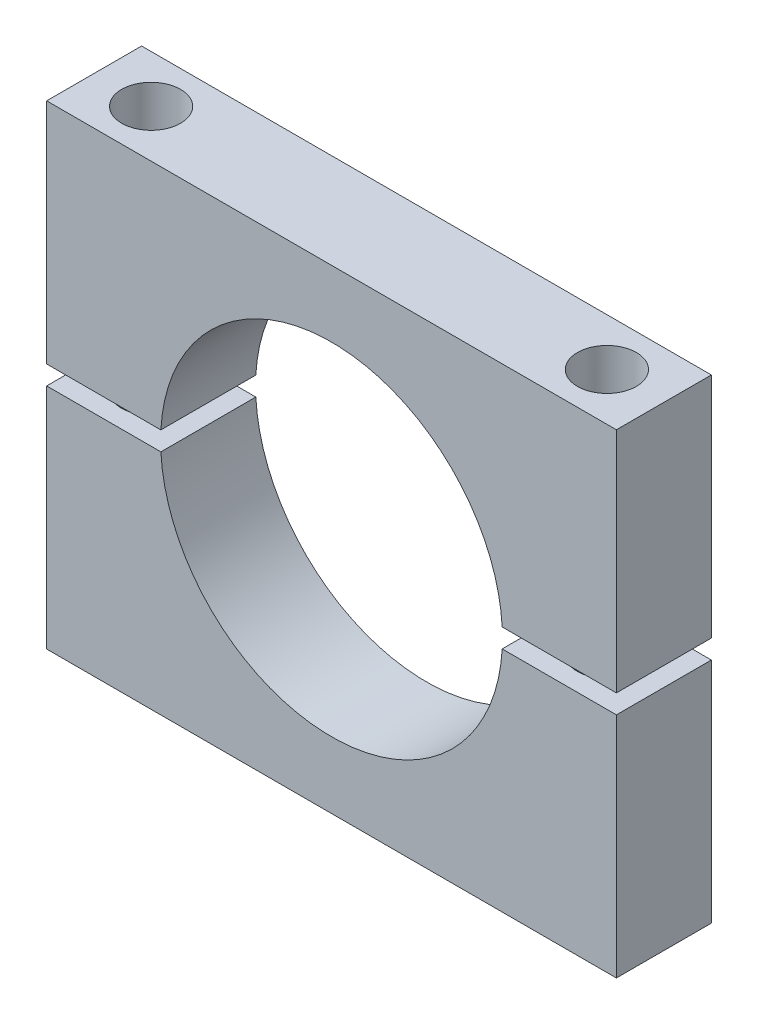
SolidWorks part; units mm, degrees
ref_plane "前视基准面" through (0, 0, 0) normal (0, 0, 1) x (1, 0, 0)
ref_plane "上视基准面" through (0, 0, 0) normal (0, 1, 0) x (1, 0, 0)
ref_plane "右视基准面" through (0, 0, 0) normal (1, 0, 0) x (0, 0, -1)
sketch "草图1" plane through (0, 0, 0) normal (0, 1, 0) x (1, 0, 0)
  line L1 (15, -2.5) -> (-15, -2.5)
  line L2 (15, -2.5) -> (15, 2.5)
  line L3 (15, 2.5) -> (-15, 2.5)
  line L4 (-15, -2.5) -> (-15, 2.5)
  line L5 (15, -2.5) -> (-15, 2.5) construction
  line L6 (15, 2.5) -> (-15, -2.5) construction
  point P0 (0, 0)
  dimension "D1" = 5
  dimension "D2" = 30
extrude "凸台-拉伸1" add sketch "草图1" along normal blind 25
sketch "草图2" plane through (0, 0, 2.5) normal (0, 0, 1) x (1, 0, 0)
  line L0 (15, 25) -> (-15, 0) construction
  line L1 (-15, 25) -> (15, 0) construction
  line L2 (-15, 12.5) -> (15, 12.5) construction
  line L3 (-15, 25) -> (-15, 0) construction
  line L4 (15, 25) -> (15, 0) construction
  line L5 (-15, 12) -> (-8.9861, 12)
  line L6 (-15, 13) -> (-8.9861, 13)
  line L7 (15, 13) -> (15, 12)
  line L8 (-15, 13) -> (-15, 12)
  line L10 (-15, 13) -> (15, 13) construction
  line L12 (-15, 12) -> (15, 12) construction
  line L13 (8.9861, 13) -> (15, 13)
  line L14 (8.9861, 12) -> (15, 12)
  arc A0 (-8.9861, 12) -> (8.9861, 12) centre (0, 12.5) ccw
  arc A1 (8.9861, 13) -> (-8.9861, 13) centre (0, 12.5) ccw
  dimension "D1" = 18
  dimension "D2" = 0.5
  dimension "D3" = 0.5
extrude "切除-拉伸1" cut sketch "草图2" against normal blind 21
sketch "草图3" plane through (0, 25, 0) normal (0, 1, 0) x (1, 0, 0)
  line L0 (-15, 0) -> (0, 0) construction
  line L1 (-15, 2.5) -> (-15, -2.5) construction
  line L2 (0, 0) -> (0, 3.0423) construction
  circle A0 centre (-12, 0) radius 1.55
  circle A1 centre (12, 0) radius 1.55
  dimension "D2" = 3.1
  dimension "D1" = 24
extrude "切除-拉伸2" cut sketch "草图3" against normal blind 41
